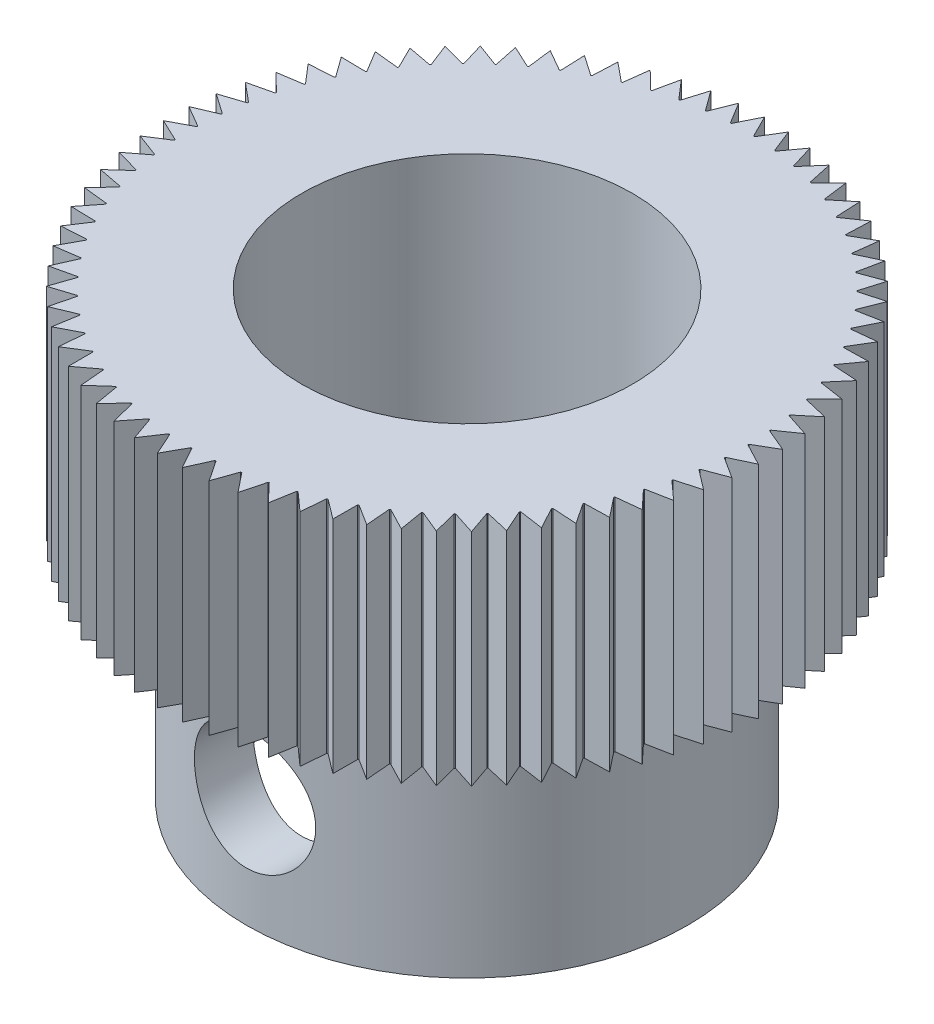
SolidWorks part; units mm, degrees
ref_plane "Front Plane" through (0, 0, 0) normal (0, 0, 1) x (1, 0, 0)
ref_plane "Top Plane" through (0, 0, 0) normal (0, 1, 0) x (1, 0, 0)
ref_plane "Right Plane" through (0, 0, 0) normal (1, 0, 0) x (0, 0, -1)
sketch "Sketch1" plane through (0, 0, 0) normal (0, 1, 0) x (1, 0, 0)
  circle A0 centre (0, 0) radius 5
  dimension "D1" = 10
extrude "Boss-Extrude1" add sketch "Sketch1" along normal blind 4
sketch "Sketch3" plane through (0, 4, 0) normal (0, 1, 0) x (1, 0, 0)
  line L0 (-0.2, 4.996) -> (0.2, 4.996)
  line L1 (-0.2, 4.996) -> (0, 5.396)
  line L2 (0, 5.396) -> (0.2, 4.996)
  line L3 (0.2188, 4.9952) -> (0.4515, 5.3771)
  line L4 (0.4515, 5.3771) -> (0.6174, 4.9617)
  line L5 (0.2188, 4.9952) -> (0.6174, 4.9617)
  line L6 (0.636, 4.9594) -> (0.8999, 5.3204)
  line L7 (0.8999, 5.3204) -> (1.0304, 4.8927)
  line L8 (0.636, 4.9594) -> (1.0304, 4.8927)
  line L9 (1.0487, 4.8888) -> (1.3419, 5.2265)
  line L10 (1.3419, 5.2265) -> (1.4362, 4.7893)
  line L11 (1.0487, 4.8888) -> (1.4362, 4.7893)
  line L12 (1.4541, 4.7839) -> (1.7746, 5.0959)
  line L13 (1.7746, 5.0959) -> (1.8319, 4.6523)
  line L14 (1.4541, 4.7839) -> (1.8319, 4.6523)
  line L15 (1.8493, 4.6454) -> (2.1948, 4.9295)
  line L16 (2.1948, 4.9295) -> (2.2148, 4.4827)
  line L17 (1.8493, 4.6454) -> (2.2148, 4.4827)
  line L18 (2.2316, 4.4744) -> (2.5995, 4.7285)
  line L19 (2.5995, 4.7285) -> (2.5821, 4.2817)
  line L20 (2.2316, 4.4744) -> (2.5821, 4.2817)
  line L21 (2.5982, 4.272) -> (2.9861, 4.4944)
  line L22 (2.9861, 4.4944) -> (2.9313, 4.0506)
  line L23 (2.5982, 4.272) -> (2.9313, 4.0506)
  line L24 (2.9465, 4.0396) -> (3.3517, 4.2288)
  line L25 (3.3517, 4.2288) -> (3.26, 3.7911)
  line L26 (2.9465, 4.0396) -> (3.26, 3.7911)
  line L27 (3.2742, 3.7788) -> (3.6938, 3.9335)
  line L28 (3.6938, 3.9335) -> (3.5658, 3.505)
  line L29 (3.2742, 3.7788) -> (3.5658, 3.505)
  line L30 (3.5789, 3.4916) -> (4.01, 3.6106)
  line L31 (4.01, 3.6106) -> (3.8466, 3.1943)
  line L32 (3.5789, 3.4916) -> (3.8466, 3.1943)
  line L33 (3.8585, 3.1799) -> (4.2981, 3.2624)
  line L34 (4.2981, 3.2624) -> (4.1004, 2.8613)
  line L35 (3.8585, 3.1799) -> (4.1004, 2.8613)
  line L36 (4.1111, 2.8459) -> (4.556, 2.8913)
  line L37 (4.556, 2.8913) -> (4.3254, 2.5081)
  line L38 (4.1111, 2.8459) -> (4.3254, 2.5081)
  line L39 (4.3348, 2.4919) -> (4.782, 2.4999)
  line L40 (4.782, 2.4999) -> (4.5201, 2.1374)
  line L41 (4.3348, 2.4919) -> (4.5201, 2.1374)
  line L42 (4.5281, 2.1204) -> (4.9744, 2.091)
  line L43 (4.9744, 2.091) -> (4.6831, 1.7517)
  line L44 (4.5281, 2.1204) -> (4.6831, 1.7517)
  line L45 (4.6897, 1.7341) -> (5.1319, 1.6675)
  line L46 (5.1319, 1.6675) -> (4.8133, 1.3536)
  line L47 (4.6897, 1.7341) -> (4.8133, 1.3536)
  line L48 (4.8183, 1.3356) -> (5.2534, 1.2322)
  line L49 (5.2534, 1.2322) -> (4.9097, 0.9461)
  line L50 (4.8183, 1.3356) -> (4.9097, 0.9461)
  line L51 (4.9132, 0.9277) -> (5.3381, 0.7883)
  line L52 (5.3381, 0.7883) -> (4.9716, 0.532)
  line L53 (4.9132, 0.9277) -> (4.9716, 0.532)
  line L54 (4.9736, 0.5133) -> (5.3854, 0.3388)
  line L55 (5.3854, 0.3388) -> (4.9987, 0.1141)
  line L56 (4.9736, 0.5133) -> (4.9987, 0.1141)
  line L57 (4.9991, 0.0953) -> (5.3948, -0.113)
  line L58 (5.3948, -0.113) -> (4.9907, -0.3046)
  line L59 (4.9991, 0.0953) -> (4.9907, -0.3046)
  line L60 (4.9895, -0.3233) -> (5.3664, -0.564)
  line L61 (5.3664, -0.564) -> (4.9477, -0.7211)
  line L62 (4.9895, -0.3233) -> (4.9477, -0.7211)
  line L63 (4.945, -0.7397) -> (5.3004, -1.0111)
  line L64 (5.3004, -1.0111) -> (4.87, -1.1326)
  line L65 (4.945, -0.7397) -> (4.87, -1.1326)
  line L66 (4.8657, -1.1509) -> (5.1972, -1.4511)
  line L67 (5.1972, -1.4511) -> (4.7582, -1.5362)
  line L68 (4.8657, -1.1509) -> (4.7582, -1.5362)
  line L69 (4.7524, -1.554) -> (5.0576, -1.8809)
  line L70 (5.0576, -1.8809) -> (4.6129, -1.9289)
  line L71 (4.7524, -1.554) -> (4.6129, -1.9289)
  line L72 (4.6057, -1.9462) -> (4.8824, -2.2975)
  line L73 (4.8824, -2.2975) -> (4.4354, -2.3082)
  line L74 (4.6057, -1.9462) -> (4.4354, -2.3082)
  line L75 (4.4267, -2.3248) -> (4.6731, -2.698)
  line L76 (4.6731, -2.698) -> (4.2267, -2.6712)
  line L77 (4.4267, -2.3248) -> (4.2267, -2.6712)
  line L78 (4.2166, -2.6871) -> (4.4309, -3.0796)
  line L79 (4.4309, -3.0796) -> (3.9883, -3.0155)
  line L80 (4.2166, -2.6871) -> (3.9883, -3.0155)
  line L81 (3.977, -3.0305) -> (4.1577, -3.4395)
  line L82 (4.1577, -3.4395) -> (3.722, -3.3387)
  line L83 (3.977, -3.0305) -> (3.722, -3.3387)
  line L84 (3.7094, -3.3526) -> (3.8553, -3.7754)
  line L85 (3.8553, -3.7754) -> (3.4296, -3.6384)
  line L86 (3.7094, -3.3526) -> (3.4296, -3.6384)
  line L87 (3.4159, -3.6513) -> (3.5259, -4.0847)
  line L88 (3.5259, -4.0847) -> (3.1131, -3.9126)
  line L89 (3.4159, -3.6513) -> (3.1131, -3.9126)
  line L90 (3.0984, -3.9243) -> (3.1717, -4.3655)
  line L91 (3.1717, -4.3655) -> (2.7748, -4.1594)
  line L92 (3.0984, -3.9243) -> (2.7748, -4.1594)
  line L93 (2.7591, -4.1698) -> (2.7953, -4.6155)
  line L94 (2.7953, -4.6155) -> (2.417, -4.377)
  line L95 (2.7591, -4.1698) -> (2.417, -4.377)
  line L96 (2.4005, -4.386) -> (2.3993, -4.8333)
  line L97 (2.3993, -4.8333) -> (2.0423, -4.5639)
  line L98 (2.4005, -4.386) -> (2.0423, -4.5639)
  line L99 (2.0251, -4.5715) -> (1.9864, -5.0171)
  line L100 (1.9864, -5.0171) -> (1.6532, -4.7188)
  line L101 (2.0251, -4.5715) -> (1.6532, -4.7188)
  line L102 (1.6355, -4.725) -> (1.5596, -5.1657)
  line L103 (1.5596, -5.1657) -> (1.2525, -4.8406)
  line L104 (1.6355, -4.725) -> (1.2525, -4.8406)
  line L105 (1.2344, -4.8452) -> (1.1219, -5.2781)
  line L106 (1.1219, -5.2781) -> (0.8431, -4.9284)
  line L107 (1.2344, -4.8452) -> (0.8431, -4.9284)
  line L108 (0.8246, -4.9315) -> (0.6763, -5.3534)
  line L109 (0.6763, -5.3534) -> (0.4277, -4.9817)
  line L110 (0.8246, -4.9315) -> (0.4277, -4.9817)
  line L111 (0.409, -4.9832) -> (0.226, -5.3913)
  line L112 (0.226, -5.3913) -> (0.0094, -5)
  line L113 (0.409, -4.9832) -> (0.0094, -5)
  line L114 (-0.0094, -5) -> (-0.226, -5.3913)
  line L115 (-0.226, -5.3913) -> (-0.409, -4.9832)
  line L116 (-0.0094, -5) -> (-0.409, -4.9832)
  line L117 (-0.4277, -4.9817) -> (-0.6763, -5.3534)
  line L118 (-0.6763, -5.3534) -> (-0.8246, -4.9315)
  line L119 (-0.4277, -4.9817) -> (-0.8246, -4.9315)
  line L120 (-0.8431, -4.9284) -> (-1.1219, -5.2781)
  line L121 (-1.1219, -5.2781) -> (-1.2344, -4.8452)
  line L122 (-0.8431, -4.9284) -> (-1.2344, -4.8452)
  line L123 (-1.2525, -4.8406) -> (-1.5596, -5.1657)
  line L124 (-1.5596, -5.1657) -> (-1.6355, -4.725)
  line L125 (-1.2525, -4.8406) -> (-1.6355, -4.725)
  line L126 (-1.6532, -4.7188) -> (-1.9864, -5.0171)
  line L127 (-1.9864, -5.0171) -> (-2.0251, -4.5715)
  line L128 (-1.6532, -4.7188) -> (-2.0251, -4.5715)
  line L129 (-2.0423, -4.5639) -> (-2.3993, -4.8333)
  line L130 (-2.3993, -4.8333) -> (-2.4005, -4.386)
  line L131 (-2.0423, -4.5639) -> (-2.4005, -4.386)
  line L132 (-2.417, -4.377) -> (-2.7953, -4.6155)
  line L133 (-2.7953, -4.6155) -> (-2.7591, -4.1698)
  line L134 (-2.417, -4.377) -> (-2.7591, -4.1698)
  line L135 (-2.7748, -4.1594) -> (-3.1717, -4.3655)
  line L136 (-3.1717, -4.3655) -> (-3.0984, -3.9243)
  line L137 (-2.7748, -4.1594) -> (-3.0984, -3.9243)
  line L138 (-3.1131, -3.9126) -> (-3.5259, -4.0847)
  line L139 (-3.5259, -4.0847) -> (-3.4159, -3.6513)
  line L140 (-3.1131, -3.9126) -> (-3.4159, -3.6513)
  line L141 (-3.4296, -3.6384) -> (-3.8553, -3.7754)
  line L142 (-3.8553, -3.7754) -> (-3.7094, -3.3526)
  line L143 (-3.4296, -3.6384) -> (-3.7094, -3.3526)
  line L144 (-3.722, -3.3387) -> (-4.1577, -3.4395)
  line L145 (-4.1577, -3.4395) -> (-3.977, -3.0305)
  line L146 (-3.722, -3.3387) -> (-3.977, -3.0305)
  line L147 (-3.9883, -3.0155) -> (-4.4309, -3.0796)
  line L148 (-4.4309, -3.0796) -> (-4.2166, -2.6871)
  line L149 (-3.9883, -3.0155) -> (-4.2166, -2.6871)
  line L150 (-4.2267, -2.6712) -> (-4.6731, -2.698)
  line L151 (-4.6731, -2.698) -> (-4.4267, -2.3248)
  line L152 (-4.2267, -2.6712) -> (-4.4267, -2.3248)
  line L153 (-4.4354, -2.3082) -> (-4.8824, -2.2975)
  line L154 (-4.8824, -2.2975) -> (-4.6057, -1.9462)
  line L155 (-4.4354, -2.3082) -> (-4.6057, -1.9462)
  line L156 (-4.6129, -1.9289) -> (-5.0576, -1.8809)
  line L157 (-5.0576, -1.8809) -> (-4.7524, -1.554)
  line L158 (-4.6129, -1.9289) -> (-4.7524, -1.554)
  line L159 (-4.7582, -1.5362) -> (-5.1972, -1.4511)
  line L160 (-5.1972, -1.4511) -> (-4.8657, -1.1509)
  line L161 (-4.7582, -1.5362) -> (-4.8657, -1.1509)
  line L162 (-4.87, -1.1326) -> (-5.3004, -1.0111)
  line L163 (-5.3004, -1.0111) -> (-4.945, -0.7397)
  line L164 (-4.87, -1.1326) -> (-4.945, -0.7397)
  line L165 (-4.9477, -0.7211) -> (-5.3664, -0.564)
  line L166 (-5.3664, -0.564) -> (-4.9895, -0.3233)
  line L167 (-4.9477, -0.7211) -> (-4.9895, -0.3233)
  line L168 (-4.9907, -0.3046) -> (-5.3948, -0.113)
  line L169 (-5.3948, -0.113) -> (-4.9991, 0.0953)
  line L170 (-4.9907, -0.3046) -> (-4.9991, 0.0953)
  line L171 (-4.9987, 0.1141) -> (-5.3854, 0.3388)
  line L172 (-5.3854, 0.3388) -> (-4.9736, 0.5133)
  line L173 (-4.9987, 0.1141) -> (-4.9736, 0.5133)
  line L174 (-4.9716, 0.532) -> (-5.3381, 0.7883)
  line L175 (-5.3381, 0.7883) -> (-4.9132, 0.9277)
  line L176 (-4.9716, 0.532) -> (-4.9132, 0.9277)
  line L177 (-4.9097, 0.9461) -> (-5.2534, 1.2322)
  line L178 (-5.2534, 1.2322) -> (-4.8183, 1.3356)
  line L179 (-4.9097, 0.9461) -> (-4.8183, 1.3356)
  line L180 (-4.8133, 1.3536) -> (-5.1319, 1.6675)
  line L181 (-5.1319, 1.6675) -> (-4.6897, 1.7341)
  line L182 (-4.8133, 1.3536) -> (-4.6897, 1.7341)
  line L183 (-4.6831, 1.7517) -> (-4.9744, 2.091)
  line L184 (-4.9744, 2.091) -> (-4.5281, 2.1204)
  line L185 (-4.6831, 1.7517) -> (-4.5281, 2.1204)
  line L186 (-4.5201, 2.1374) -> (-4.782, 2.4999)
  line L187 (-4.782, 2.4999) -> (-4.3348, 2.4919)
  line L188 (-4.5201, 2.1374) -> (-4.3348, 2.4919)
  line L189 (-4.3254, 2.5081) -> (-4.556, 2.8913)
  line L190 (-4.556, 2.8913) -> (-4.1111, 2.8459)
  line L191 (-4.3254, 2.5081) -> (-4.1111, 2.8459)
  line L192 (-4.1004, 2.8613) -> (-4.2981, 3.2624)
  line L193 (-4.2981, 3.2624) -> (-3.8585, 3.1799)
  line L194 (-4.1004, 2.8613) -> (-3.8585, 3.1799)
  line L195 (-3.8466, 3.1943) -> (-4.01, 3.6106)
  line L196 (-4.01, 3.6106) -> (-3.5789, 3.4916)
  line L197 (-3.8466, 3.1943) -> (-3.5789, 3.4916)
  line L198 (-3.5658, 3.505) -> (-3.6938, 3.9335)
  line L199 (-3.6938, 3.9335) -> (-3.2742, 3.7788)
  line L200 (-3.5658, 3.505) -> (-3.2742, 3.7788)
  line L201 (-3.26, 3.7911) -> (-3.3517, 4.2288)
  line L202 (-3.3517, 4.2288) -> (-2.9465, 4.0396)
  line L203 (-3.26, 3.7911) -> (-2.9465, 4.0396)
  line L204 (-2.9313, 4.0506) -> (-2.9861, 4.4944)
  line L205 (-2.9861, 4.4944) -> (-2.5982, 4.272)
  line L206 (-2.9313, 4.0506) -> (-2.5982, 4.272)
  line L207 (-2.5821, 4.2817) -> (-2.5995, 4.7285)
  line L208 (-2.5995, 4.7285) -> (-2.2316, 4.4744)
  line L209 (-2.5821, 4.2817) -> (-2.2316, 4.4744)
  line L210 (-2.2148, 4.4827) -> (-2.1948, 4.9295)
  line L211 (-2.1948, 4.9295) -> (-1.8493, 4.6454)
  line L212 (-2.2148, 4.4827) -> (-1.8493, 4.6454)
  line L213 (-1.8319, 4.6523) -> (-1.7746, 5.0959)
  line L214 (-1.7746, 5.0959) -> (-1.4541, 4.7839)
  line L215 (-1.8319, 4.6523) -> (-1.4541, 4.7839)
  line L216 (-1.4362, 4.7893) -> (-1.3419, 5.2265)
  line L217 (-1.3419, 5.2265) -> (-1.0487, 4.8888)
  line L218 (-1.4362, 4.7893) -> (-1.0487, 4.8888)
  line L219 (-1.0304, 4.8927) -> (-0.8999, 5.3204)
  line L220 (-0.8999, 5.3204) -> (-0.636, 4.9594)
  line L221 (-1.0304, 4.8927) -> (-0.636, 4.9594)
  line L222 (-0.6174, 4.9617) -> (-0.4515, 5.3771)
  line L223 (-0.4515, 5.3771) -> (-0.2188, 4.9952)
  line L224 (-0.6174, 4.9617) -> (-0.2188, 4.9952)
  circle A0 centre (0, 0) radius 5 construction
  point P231 (0, 0)
  dimension "D1" = 0.4
  dimension "D2" = 0.2
  dimension "D3" = 0.4
  dimension "D4" = 75
extrude "Boss-Extrude2" add sketch "Sketch3" against normal blind 4
sketch "Sketch4" plane through (0, 0, 0) normal (0, -1, 0) x (1, 0, 0)
  point P0 (0, 0)
sketch "Sketch5" plane through (0, 0, 0) normal (0, -1, 0) x (-1, 0, 0)
  circle A0 centre (0, 0) radius 4
  dimension "D1" = 8
extrude "Boss-Extrude3" add sketch "Sketch5" along normal blind 4 contours A0
sketch "Sketch7" plane through (0, -4, 0) normal (0, -1, 0) x (-1, 0, 0)
  circle A3 centre (0, 0) radius 3
  dimension "D1" = 6
extrude "Cut-Extrude2" cut sketch "Sketch7" against normal through all
sketch "草图1" plane through (0, -4, 0) normal (0, -1, 0) x (1, 0, 0)
  line L0 (0, -4) -> (0, 4)
  circle A0 centre (0, 0) radius 4 construction
ref_plane "基准面1" through (0, 0, 4) normal (0, 0, 1) x (1, 0, 0)
sketch "草图2" plane through (0, 0, 4) normal (0, 0, 1) x (1, 0, 0)
  line L0 (0, -4) -> (0, 0)
  circle A0 centre (0, -2) radius 1.1
extrude "切除-拉伸1" cut sketch "草图2" against normal through all contours A0
